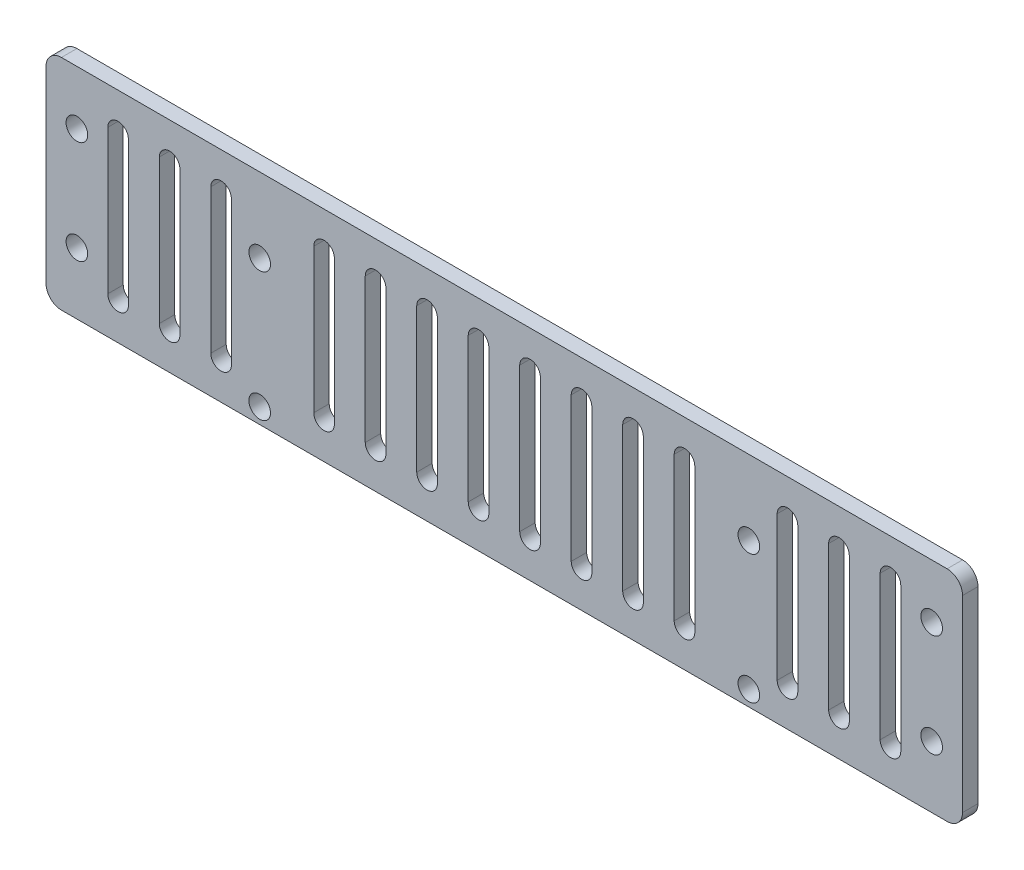
SolidWorks part; units mm, degrees
material "Thornel Mat VMA"
ref_plane "前视基准面" through (0, 0, 0) normal (0, 0, 1) x (1, 0, 0)
ref_plane "上视基准面" through (0, 0, 0) normal (0, 1, 0) x (1, 0, 0)
ref_plane "右视基准面" through (0, 0, 0) normal (1, 0, 0) x (0, 0, -1)
other "Configuration Table"
sketch "草图1" plane through (0, 0, 0) normal (0, 0, 1) x (1, 0, 0)
  line L0 (0, 26.2512) -> (0, -16.2488) construction
  line L1 (89, -16.2488) -> (-89, -16.2488)
  line L2 (89, -16.2488) -> (89, 26.2512)
  line L3 (89, 26.2512) -> (-89, 26.2512)
  line L4 (-89, -16.2488) -> (-89, 26.2512)
  line L5 (89, -16.2488) -> (-89, 26.2512) construction
  line L6 (89, 26.2512) -> (-89, -16.2488) construction
  line L7 (-83, 26.2512) -> (-83, -16.2488) construction
  line L9 (47.5, -13.2488) -> (-47.5, -13.2488) construction
  line L10 (47.5, -13.2488) -> (47.5, 11.7512) construction
  line L11 (47.5, 11.7512) -> (-47.5, 11.7512) construction
  line L12 (-47.5, -13.2488) -> (-47.5, 11.7512) construction
  line L13 (47.5, -13.2488) -> (-47.5, 11.7512) construction
  line L14 (47.5, 11.7512) -> (-47.5, -13.2488) construction
  circle A0 centre (-83, 15.7512) radius 2.1
  circle A1 centre (-83, -4.2488) radius 2.1
  circle A2 centre (-47.5, 11.7512) radius 2.1
  circle A3 centre (47.5, 11.7512) radius 2.1
  circle A4 centre (47.5, -13.2488) radius 2.1
  circle A5 centre (-47.5, -13.2488) radius 2.1
  circle A6 centre (83, -4.2488) radius 2.1
  circle A7 centre (83, 15.7512) radius 2.1
  point P0 (0, 0)
  point P14 (0, 0)
  dimension "D3" = 4.2
  dimension "D4" = 20
  dimension "D5" = 12
  dimension "D9" = 4.2
  dimension "D10" = 3
  dimension "D1" = 178
  dimension "D2" = 42.5
  dimension "D6" = 6
  dimension "D7" = 25
  dimension "D8" = 95
extrude "凸台-拉伸1" add sketch "草图1" along normal blind 3
fillet "圆角1" radius 3 4 edges at (89, 26.2512, 1.5) (89, -16.2488, 1.5) (-89, -16.2488, 1.5) (-89, 26.2512, 1.5)
sketch "草图2" plane through (0, 0, 3) normal (0, 0, 1) x (1, 0, 0)
  line L0 (-75, 19.0012) -> (-75, -8.9988) construction
  line L1 (-73, 19.0012) -> (-73, -8.9988)
  line L2 (-77, 19.0012) -> (-77, -8.9988)
  line L3 (-89, 5.0012) -> (89, 5.0012) construction
  line L6 (-89, 23.2512) -> (-89, -13.2488) construction
  line L7 (89, -13.2488) -> (89, 23.2512) construction
  line L8 (-67, 19.0012) -> (-67, -8.9988)
  line L9 (-63, 19.0012) -> (-63, -8.9988)
  line L10 (-65, 19.0012) -> (-65, -8.9988) construction
  line L11 (-57, 19.0012) -> (-57, -8.9988)
  line L12 (-53, 19.0012) -> (-53, -8.9988)
  line L13 (-55, 19.0012) -> (-55, -8.9988) construction
  line L17 (-37, 19.0012) -> (-37, -8.9988)
  line L18 (-33, 19.0012) -> (-33, -8.9988)
  line L19 (-35, 19.0012) -> (-35, -8.9988) construction
  line L20 (-27, 19.0012) -> (-27, -8.9988)
  line L21 (-23, 19.0012) -> (-23, -8.9988)
  line L22 (-25, 19.0012) -> (-25, -8.9988) construction
  line L23 (-17, 19.0012) -> (-17, -8.9988)
  line L24 (-13, 19.0012) -> (-13, -8.9988)
  line L25 (-15, 19.0012) -> (-15, -8.9988) construction
  line L26 (-7, 19.0012) -> (-7, -8.9988)
  line L27 (-3, 19.0012) -> (-3, -8.9988)
  line L28 (-5, 19.0012) -> (-5, -8.9988) construction
  line L29 (3, 19.0012) -> (3, -8.9988)
  line L30 (7, 19.0012) -> (7, -8.9988)
  line L31 (5, 19.0012) -> (5, -8.9988) construction
  line L32 (13, 19.0012) -> (13, -8.9988)
  line L33 (17, 19.0012) -> (17, -8.9988)
  line L34 (15, 19.0012) -> (15, -8.9988) construction
  line L35 (23, 19.0012) -> (23, -8.9988)
  line L36 (27, 19.0012) -> (27, -8.9988)
  line L37 (25, 19.0012) -> (25, -8.9988) construction
  line L38 (33, 19.0012) -> (33, -8.9988)
  line L39 (37, 19.0012) -> (37, -8.9988)
  line L40 (35, 19.0012) -> (35, -8.9988) construction
  line L44 (53, 19.0012) -> (53, -8.9988)
  line L45 (57, 19.0012) -> (57, -8.9988)
  line L46 (55, 19.0012) -> (55, -8.9988) construction
  line L47 (63, 19.0012) -> (63, -8.9988)
  line L48 (67, 19.0012) -> (67, -8.9988)
  line L49 (65, 19.0012) -> (65, -8.9988) construction
  line L50 (73, 19.0012) -> (73, -8.9988)
  line L51 (77, 19.0012) -> (77, -8.9988)
  line L52 (75, 19.0012) -> (75, -8.9988) construction
  line L53 (-43, 19.0012) -> (-43, -8.9988) [skipped]
  line L54 (-47, 19.0012) -> (-47, -8.9988) [skipped]
  line L55 (47, 19.0012) -> (47, -8.9988) [skipped]
  line L56 (43, 19.0012) -> (43, -8.9988) [skipped]
  arc A0 (-73, 19.0012) -> (-77, 19.0012) centre (-75, 19.0012) ccw
  arc A1 (-77, -8.9988) -> (-73, -8.9988) centre (-75, -8.9988) ccw
  arc A4 (-63, 19.0012) -> (-67, 19.0012) centre (-65, 19.0012) ccw
  arc A5 (-67, -8.9988) -> (-63, -8.9988) centre (-65, -8.9988) ccw
  arc A6 (-53, 19.0012) -> (-57, 19.0012) centre (-55, 19.0012) ccw
  arc A7 (-57, -8.9988) -> (-53, -8.9988) centre (-55, -8.9988) ccw
  arc A10 (-33, 19.0012) -> (-37, 19.0012) centre (-35, 19.0012) ccw
  arc A11 (-37, -8.9988) -> (-33, -8.9988) centre (-35, -8.9988) ccw
  arc A12 (-23, 19.0012) -> (-27, 19.0012) centre (-25, 19.0012) ccw
  arc A13 (-27, -8.9988) -> (-23, -8.9988) centre (-25, -8.9988) ccw
  arc A14 (-13, 19.0012) -> (-17, 19.0012) centre (-15, 19.0012) ccw
  arc A15 (-17, -8.9988) -> (-13, -8.9988) centre (-15, -8.9988) ccw
  arc A16 (-3, 19.0012) -> (-7, 19.0012) centre (-5, 19.0012) ccw
  arc A17 (-7, -8.9988) -> (-3, -8.9988) centre (-5, -8.9988) ccw
  arc A18 (7, 19.0012) -> (3, 19.0012) centre (5, 19.0012) ccw
  arc A19 (3, -8.9988) -> (7, -8.9988) centre (5, -8.9988) ccw
  arc A20 (17, 19.0012) -> (13, 19.0012) centre (15, 19.0012) ccw
  arc A21 (13, -8.9988) -> (17, -8.9988) centre (15, -8.9988) ccw
  arc A22 (27, 19.0012) -> (23, 19.0012) centre (25, 19.0012) ccw
  arc A23 (23, -8.9988) -> (27, -8.9988) centre (25, -8.9988) ccw
  arc A24 (37, 19.0012) -> (33, 19.0012) centre (35, 19.0012) ccw
  arc A25 (33, -8.9988) -> (37, -8.9988) centre (35, -8.9988) ccw
  arc A28 (57, 19.0012) -> (53, 19.0012) centre (55, 19.0012) ccw
  arc A29 (53, -8.9988) -> (57, -8.9988) centre (55, -8.9988) ccw
  arc A30 (67, 19.0012) -> (63, 19.0012) centre (65, 19.0012) ccw
  arc A31 (63, -8.9988) -> (67, -8.9988) centre (65, -8.9988) ccw
  arc A32 (77, 19.0012) -> (73, 19.0012) centre (75, 19.0012) ccw
  arc A33 (73, -8.9988) -> (77, -8.9988) centre (75, -8.9988) ccw
  arc A34 (-43, 19.0012) -> (-47, 19.0012) centre (-45, 19.0012) ccw [skipped]
  arc A35 (-47, -8.9988) -> (-43, -8.9988) centre (-45, -8.9988) ccw [skipped]
  arc A36 (47, 19.0012) -> (43, 19.0012) centre (45, 19.0012) ccw [skipped]
  arc A37 (43, -8.9988) -> (47, -8.9988) centre (45, -8.9988) ccw [skipped]
  point P2 (-75, 5.0012)
  point P17 (-65, 5.0012)
  point P24 (-55, 5.0012)
  point P38 (-35, 5.0012)
  point P45 (-25, 5.0012)
  point P52 (-15, 5.0012)
  point P59 (-5, 5.0012)
  point P66 (5, 5.0012)
  point P73 (15, 5.0012)
  point P80 (25, 5.0012)
  point P87 (35, 5.0012)
  point P101 (55, 5.0012)
  point P108 (65, 5.0012)
  point P115 (75, 5.0012)
  dimension "D1" = 2
  dimension "D2" = 28
  dimension "D3" = 12
  dimension "D5" = 6
  dimension "D4" = 16
extrude "切除-拉伸1" cut sketch "草图2" against normal blind 10
